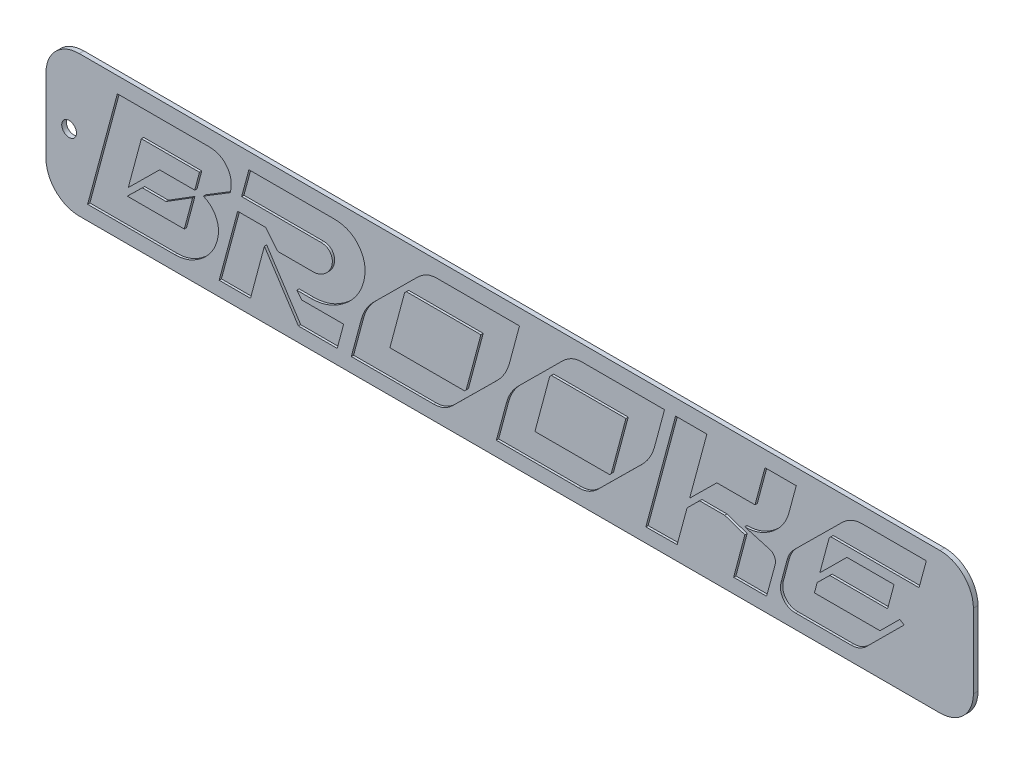
SolidWorks part; units mm, degrees
ref_plane "Front Plane" through (0, 0, 0) normal (0, 0, 1) x (1, 0, 0)
ref_plane "Top Plane" through (0, 0, 0) normal (0, 1, 0) x (1, 0, 0)
ref_plane "Right Plane" through (0, 0, 0) normal (1, 0, 0) x (0, 0, -1)
sketch "Sketch4" plane through (0, 0, 0) normal (0, 0, 1) x (1, 0, 0)
  line L0 (-33.5743, 38.5691) -> (-21.9494, 38.5691) construction
  line L1 (-10.7143, 86.9255) -> (580.6871, 86.9255)
  line L2 (-33.5743, 64.0655) -> (-33.5743, 13.0726)
  line L3 (-10.7143, -9.7874) -> (580.6871, -9.7874)
  line L4 (603.5471, 64.0655) -> (603.5471, 13.0726)
  arc A0 (580.6871, -9.7874) -> (603.5471, 13.0726) centre (580.6871, 13.0726) ccw
  arc A1 (580.6871, 86.9255) -> (603.5471, 64.0655) centre (580.6871, 64.0655) cw
  arc A2 (-33.5743, 13.0726) -> (-10.7143, -9.7874) centre (-10.7143, 13.0726) ccw
  arc A3 (-10.7143, 86.9255) -> (-33.5743, 64.0655) centre (-10.7143, 64.0655) ccw
  circle A4 centre (-21.9494, 38.5691) radius 3.302
  text T0 "brooke" font "Sterion" height 76.2
  dimension "D1" = 22.86
extrude "Boss-Extrude2" add sketch "Sketch4" along normal blind 3.175 contours L2 A2 L3 A0 L4 A1 L1 A3
sketch "Sketch5" plane through (0, 0, 3.175) normal (0, 0, 1) x (1, 0, 0)
  text T0 "brooke" font "Sterion" height 76.2
extrude "Cut-Extrude2" cut sketch "Sketch5" against normal blind 1.5875
sketch "Sketch6" plane through (0, 0, 3.175) normal (0, 0, 1) x (1, 0, 0)
  line L0 (-33.5743, 38.5691) -> (-17.705, 38.5691) construction
  line L1 (-33.5743, 64.0655) -> (-33.5743, 13.0726) construction
  circle A0 centre (-17.705, 38.5691) radius 5.08
extrude "Cut-Extrude3" cut sketch "Sketch6" against normal blind 3.175
